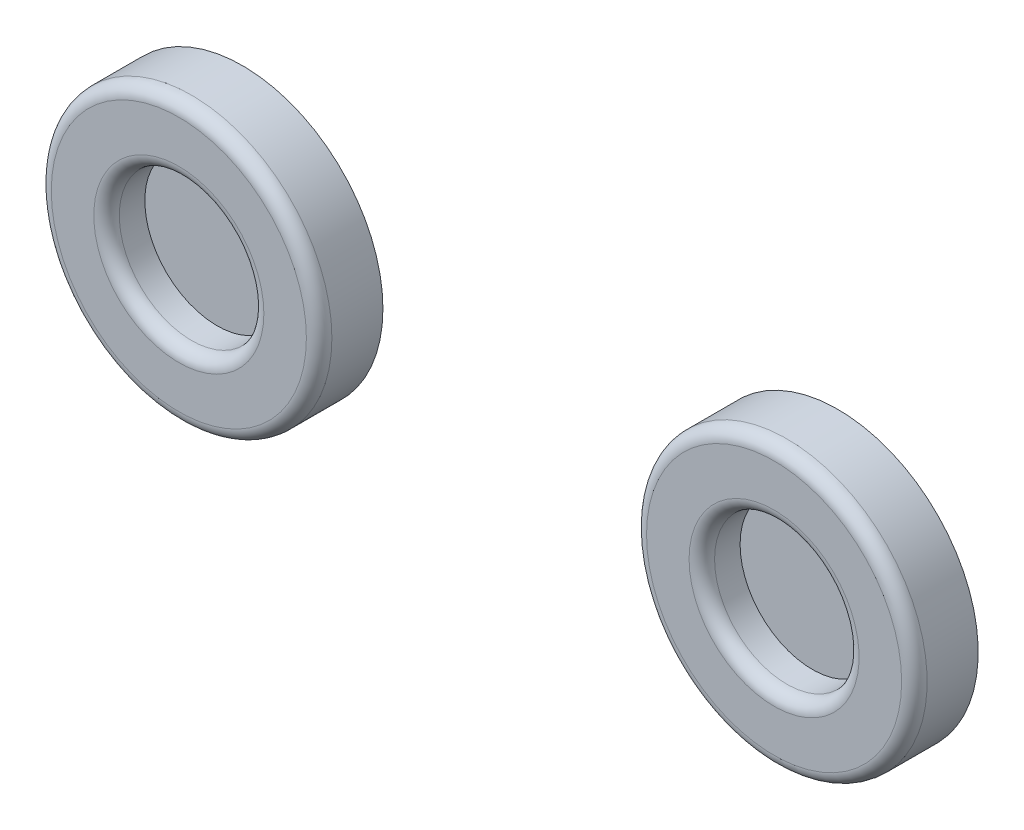
SolidWorks part; units mm, degrees
ref_plane "Front Plane" through (0, 0, 0) normal (0, 0, 1) x (1, 0, 0)
ref_plane "Top Plane" through (0, 0, 0) normal (0, 1, 0) x (1, 0, 0)
ref_plane "Right Plane" through (0, 0, 0) normal (1, 0, 0) x (0, 0, -1)
sketch "Sketch1" plane through (0, 0, 0) normal (0, 0, 1) x (1, 0, 0)
  line L0 (0, 77.4113) -> (0, -77.4113) construction
  line L1 (-70, 0) -> (70, 0) construction
  line L2 (70, 77.4113) -> (70, -77.4113) construction
  line L3 (-70, 77.4113) -> (-70, -77.4113) construction
  circle A0 centre (-70, 0) radius 33
  circle A1 centre (70, 0) radius 33
  point P10 (0, 0)
  point P11 (0, 0)
  point P12 (0, 0)
  point P13 (0, 0)
  point P14 (0, 0)
  point P15 (0, 0)
  point P16 (0, 0)
  point P17 (0, 0)
  point P18 (0, 0)
  point P19 (0, 0)
  point P20 (0, 0)
  point P21 (0, 0)
  point P22 (0, 0)
  point P23 (0, 0)
  point P24 (0, 0)
  point P25 (0, 0)
  point P26 (0, 77.4113)
  point P27 (0, 0)
  point P28 (0, 0)
  point P29 (0, 0)
  dimension "D1" = 66
extrude "Boss-Extrude1" add sketch "Sketch1" along normal blind 15
sketch "Sketch2" plane through (0, 0, 15) normal (0, 0, 1) x (1, 0, 0)
  line L0 (0, 46.5863) -> (0, -72.5066) construction
  line L1 (-103, 0) -> (-70, 0) construction
  line L2 (103, 0) -> (70, 0) construction
  circle A2 centre (-70, 0) radius 33 construction
  circle A3 centre (70, 0) radius 33 construction
  circle A4 centre (-70, 0) radius 17
  circle A5 centre (70, 0) radius 17
  dimension "D1" = 34
extrude "Cut-Extrude1" cut sketch "Sketch2" against normal blind 9
fillet "Fillet1" radius 3 1 edges at (-37, 0, 15)
fillet "Fillet2" radius 3 1 edges at (37, 0, 15)
fillet "Fillet3" radius 3 1 edges at (53, 0, 15)
fillet "Fillet4" radius 3 1 edges at (-53, 0, 15)
